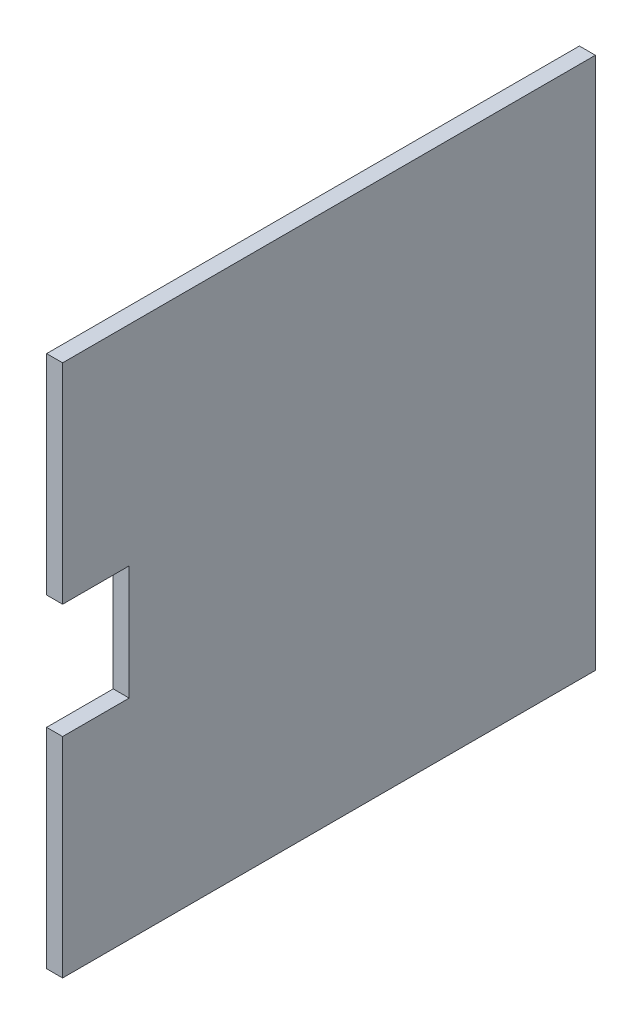
SolidWorks part; units mm, degrees
ref_plane "Front Plane" through (0, 0, 0) normal (0, 0, 1) x (1, 0, 0)
ref_plane "Top Plane" through (0, 0, 0) normal (0, 1, 0) x (1, 0, 0)
ref_plane "Right Plane" through (0, 0, 0) normal (1, 0, 0) x (0, 0, -1)
sketch "Sketch1" plane through (0, 0, 0) normal (1, 0, 0) x (0, 0, -1)
  line L0 (-81.0303, -37.5907) -> (-81.0303, -116.0907)
  line L1 (-81.0303, 83.9093) -> (118.9697, 83.9093)
  line L2 (-81.0303, 83.9093) -> (-81.0303, 5.4093)
  line L3 (-81.0303, -116.0907) -> (118.9697, -116.0907)
  line L4 (118.9697, 83.9093) -> (118.9697, -116.0907)
  line L7 (-81.0303, 5.4093) -> (-56.0303, 5.4093)
  line L8 (-56.0303, -16.0907) -> (-56.0303, 5.4093)
  line L11 (-81.0303, -37.5907) -> (-56.0303, -37.5907)
  line L12 (-56.0303, -16.0907) -> (-56.0303, -37.5907)
  dimension "D1" = 200
  dimension "D2" = 200
  dimension "D3" = 25
  dimension "D4" = 43
extrude "Boss-Extrude1" add sketch "Sketch1" along normal blind 6
